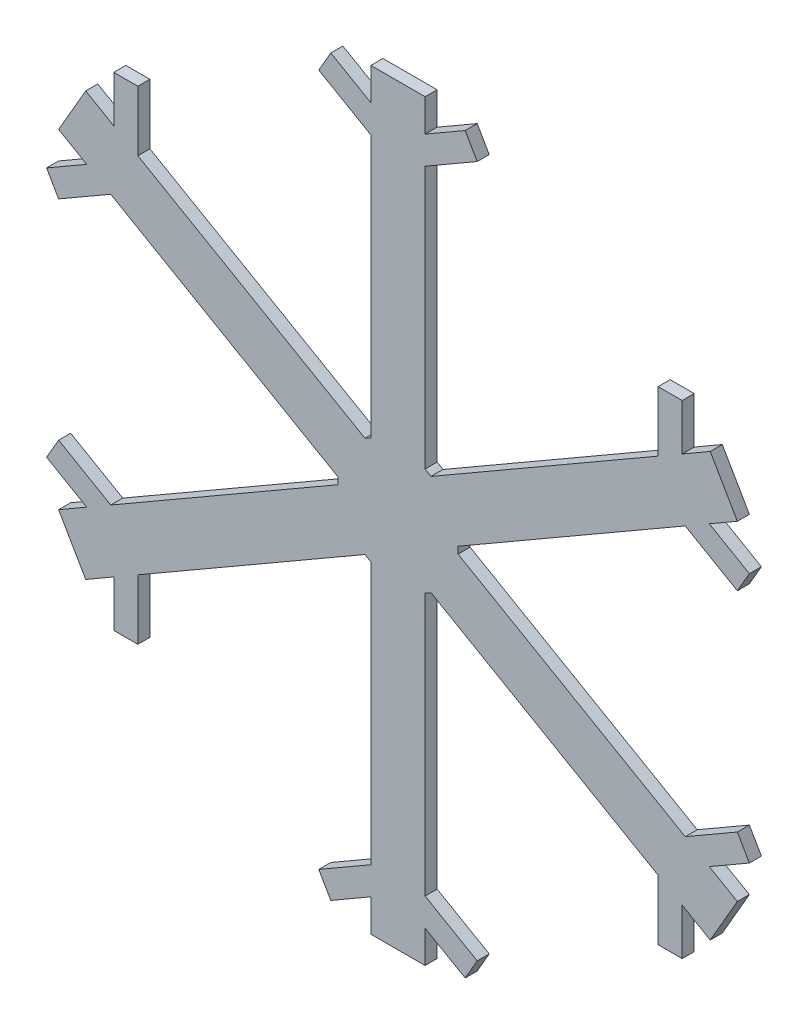
SolidWorks part; units mm, degrees
ref_plane "Front" through (0, 0, 0) normal (0, 0, 1) x (1, 0, 0)
ref_plane "Top" through (0, 0, 0) normal (0, 1, 0) x (1, 0, 0)
ref_plane "Right" through (0, 0, 0) normal (1, 0, 0) x (0, 0, -1)
sketch "Sketch2" plane through (0, 0, 0) normal (0, 0, 1) x (1, 0, 0)
  circle A1 centre (0, 0) radius 50
  dimension "D2" = 100
extrude "Boss-Extrude1" add sketch "Sketch2" against normal blind 10
sketch "Sketch3" plane through (0, 0, 0) normal (0, 0, 1) x (1, 0, 0)
  line L0 (-22.5, 0) -> (0, 0)
  line L2 (-22.5, 0) -> (-22.5, 262.5)
  line L3 (-22.5, 312.5) -> (22.5, 312.5)
  line L4 (22.5, 0) -> (22.5, 262.5)
  line L5 (0, 0) -> (22.5, 0)
  line L6 (22.5, 285.594) -> (22.5, 312.5)
  line L7 (-22.5, 262.5) -> (22.5, 262.5) construction
  line L8 (22.5, 262.5) -> (65.8013, 287.5)
  line L9 (0, 262.5) -> (0, 312.5) construction
  line L10 (65.8013, 287.5) -> (55.8013, 304.8205)
  line L11 (55.8013, 304.8205) -> (22.5, 285.594)
  line L12 (-22.5, 312.5) -> (-22.5, 285.594)
  line L13 (-55.8013, 304.8205) -> (-22.5, 285.594)
  line L14 (-65.8013, 287.5) -> (-55.8013, 304.8205)
  line L15 (-22.5, 262.5) -> (-65.8013, 287.5)
  circle A2 centre (0, 0) radius 307.5 construction
  dimension "D3" = 50
  dimension "D4" = 50
  dimension "D1" = 45
  dimension "D2" = 312.5
  dimension "D5" = 60
  dimension "D6" = 90
  dimension "D7" = 90
  dimension "D8" = 20
extrude "Boss-Extrude2" add sketch "Sketch3" against normal blind 10
pattern_circular "CirPattern1" count 6 over 360 about axis through (0, 0, 0) along (0, 0, 1) of "Boss-Extrude2"
